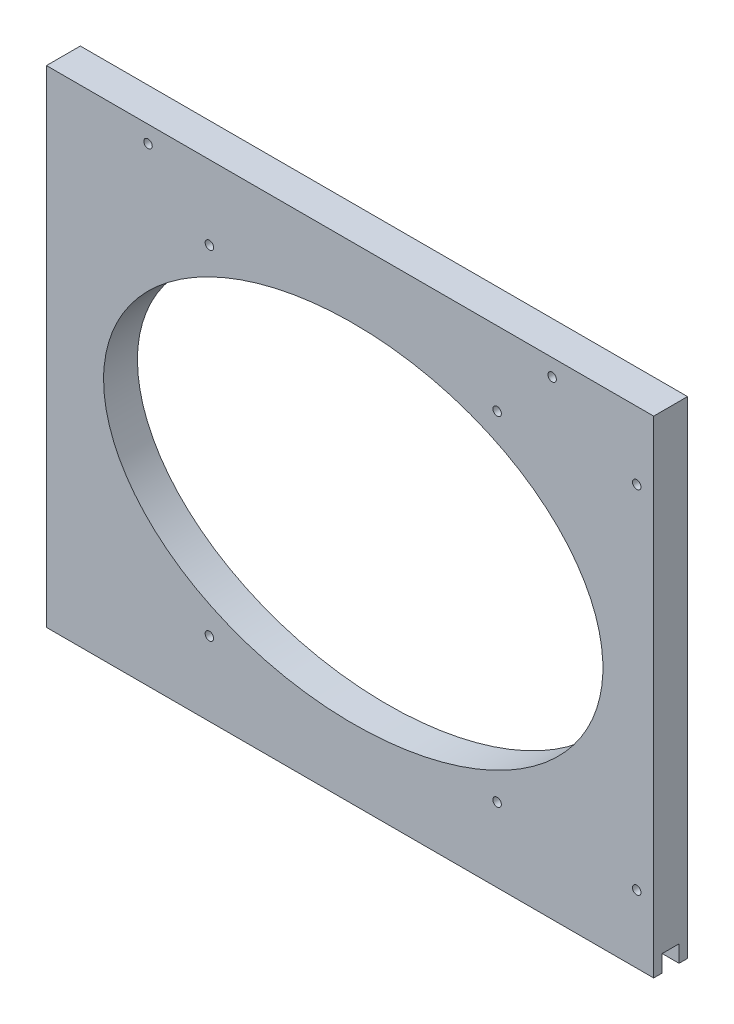
SolidWorks part; units mm, degrees
material "Pine"
ref_plane "Front Plane" through (0, 0, 0) normal (0, 0, 1) x (1, 0, 0)
ref_plane "Top Plane" through (0, 0, 0) normal (0, 1, 0) x (1, 0, 0)
ref_plane "Right Plane" through (0, 0, 0) normal (1, 0, 0) x (0, 0, -1)
sketch "Sketch1" plane through (0, 0, 0) normal (0, 0, 1) x (1, 0, 0)
  line L0 (-5300.6625, 1520.825) -> (-5451.475, 1520.825)
  line L1 (-5456.2375, 1384.3) -> (-5456.2375, 1516.0625)
  line L2 (-5557.8375, 1546.225) -> (-5194.3, 1546.225)
  line L3 (-5557.8375, 1539.875) -> (-5194.3, 1539.875)
  line L4 (-5297.4875, 1377.95) -> (-5454.65, 1377.95)
  line L5 (-5291.1375, 1384.3) -> (-5291.1375, 1516.0625)
  line L6 (-5300.6625, 1525.5875) -> (-5451.475, 1525.5875)
  line L7 (-5461, 1384.3) -> (-5461, 1516.0625)
  line L8 (-5297.4875, 1382.7125) -> (-5454.65, 1382.7125)
  line L9 (-5295.9, 1384.3) -> (-5295.9, 1516.0625)
  line L10 (-5740.4, 998.5375) -> (-5740.4, 1181.1)
  line L11 (-5740.4, 1181.1) -> (-5512.5938, 1181.1)
  line L12 (-5512.5938, 1181.1) -> (-5512.5938, 998.5375)
  line L13 (-5512.5938, 998.5375) -> (-5740.4, 998.5375)
  line L14 (-5258.5938, 1181.1) -> (-5486.4, 1181.1)
  line L15 (-5258.5938, 998.5375) -> (-5258.5938, 1181.1)
  line L16 (-5486.4, 998.5375) -> (-5258.5938, 998.5375)
  line L17 (-5486.4, 1181.1) -> (-5486.4, 998.5375)
  line L18 (-5740.4, 898.525) -> (-5011.7375, 898.525)
  line L19 (-5168.1062, 1384.3) -> (-5168.1062, 1392.2375)
  line L20 (-5176.0437, 1400.175) -> (-5245.8937, 1400.175)
  line L21 (-5253.8313, 1392.2375) -> (-5253.8313, 1384.3)
  line L22 (-5451.475, 1512.8875) -> (-5451.475, 1384.3)
  line L23 (-5303.8375, 1516.0625) -> (-5448.3, 1516.0625)
  line L24 (-5498.3062, 1384.3) -> (-5451.475, 1384.3)
  line L25 (-5253.8313, 1384.3) -> (-5300.6625, 1384.3)
  line L26 (-5584.0312, 1384.3) -> (-5740.4, 1384.3)
  line L27 (-5564.1875, 1536.7) -> (-5740.4, 1536.7)
  line L28 (-5740.4, 1357.3125) -> (-5740.4, 1206.5)
  line L29 (-5011.7375, 1357.3125) -> (-5740.4, 1357.3125)
  line L30 (-5011.7375, 1206.5) -> (-5011.7375, 1357.3125)
  line L31 (-5740.4, 1206.5) -> (-5011.7375, 1206.5)
  line L32 (-4765.675, 1549.4) -> (-4978.4, 1549.4)
  line L33 (-4765.675, 1397) -> (-4765.675, 1549.4)
  line L34 (-4978.4, 1397) -> (-4765.675, 1397)
  line L35 (-4978.4, 1549.4) -> (-4978.4, 1397)
  line L36 (-4765.675, 1371.6) -> (-4978.4, 1371.6)
  line L37 (-4765.675, 1219.2) -> (-4765.675, 1371.6)
  line L38 (-4978.4, 1219.2) -> (-4765.675, 1219.2)
  line L39 (-4978.4, 1371.6) -> (-4978.4, 1219.2)
  line L40 (-5284.7875, 803.275) -> (-5272.0875, 803.275)
  line L41 (-5187.95, 1536.7) -> (-5011.7375, 1536.7)
  line L42 (-5300.6625, 1384.3) -> (-5300.6625, 1512.8875)
  line L43 (-5740.4, 1536.7) -> (-5740.4, 1384.3)
  line L44 (-5557.8375, 1536.7) -> (-5557.8375, 1549.4)
  line L45 (-5557.8375, 1549.4) -> (-5194.3, 1549.4)
  line L46 (-5194.3, 1549.4) -> (-5194.3, 1536.7)
  line L47 (-5011.7375, 1536.7) -> (-5011.7375, 1384.3)
  line L48 (-5011.7375, 1384.3) -> (-5168.1062, 1384.3)
  line L49 (-5498.3062, 1384.3) -> (-5498.3062, 1392.2375)
  line L50 (-5506.2437, 1400.175) -> (-5576.0938, 1400.175)
  line L51 (-5584.0312, 1392.2375) -> (-5584.0312, 1384.3)
  line L52 (-5740.4, 660.4) -> (-5740.4, 898.525)
  line L53 (-5011.7375, 898.525) -> (-5011.7375, 660.4)
  line L54 (-5011.7375, 660.4) -> (-5740.4, 660.4)
  line L55 (-5291.1375, 803.275) -> (-5291.1375, 752.475)
  line L56 (-5265.7375, 752.475) -> (-5265.7375, 803.275)
  line L57 (-5284.7875, 752.475) -> (-5272.0875, 752.475)
  arc A0 (-5451.475, 1520.825) -> (-5456.2375, 1516.0625) centre (-5451.475, 1516.0625) ccw
  arc A1 (-5461, 1384.3) -> (-5454.65, 1377.95) centre (-5454.65, 1384.3) ccw
  arc A2 (-5297.4875, 1377.95) -> (-5291.1375, 1384.3) centre (-5297.4875, 1384.3) ccw
  circle A3 centre (-5037.9312, 1233.4875) radius 1.5875
  circle A4 centre (-5037.9312, 1328.7375) radius 1.5875
  circle A5 centre (-5714.2063, 1233.4875) radius 1.5875
  circle A6 centre (-5714.2063, 1328.7375) radius 1.5875
  circle A7 centre (-5018.0875, 1333.5) radius 1.5875
  circle A8 centre (-5018.0875, 1231.9) radius 1.5875
  circle A9 centre (-5734.05, 1231.9) radius 1.5875
  circle A10 centre (-5734.05, 1333.5) radius 1.5875
  circle A11 centre (-5734.05, 1511.3) radius 1.5875
  circle A12 centre (-5734.05, 1409.7) radius 1.5875
  circle A13 centre (-5018.0875, 1511.3) radius 1.5875
  circle A14 centre (-5018.0875, 1409.7) radius 1.5875
  arc A15 (-5557.8375, 1546.225) -> (-5557.8375, 1539.875) centre (-5557.8375, 1543.05) ccw
  arc A16 (-5194.3, 1539.875) -> (-5194.3, 1546.225) centre (-5194.3, 1543.05) ccw
  arc A17 (-5291.1375, 1516.0625) -> (-5300.6625, 1525.5875) centre (-5300.6625, 1516.0625) ccw
  arc A18 (-5451.475, 1525.5875) -> (-5461, 1516.0625) centre (-5451.475, 1516.0625) ccw
  arc A19 (-5456.2375, 1384.3) -> (-5454.65, 1382.7125) centre (-5454.65, 1384.3) ccw
  arc A20 (-5297.4875, 1382.7125) -> (-5295.9, 1384.3) centre (-5297.4875, 1384.3) ccw
  arc A21 (-5295.9, 1516.0625) -> (-5300.6625, 1520.825) centre (-5300.6625, 1516.0625) ccw
  circle A22 centre (-5702.3, 892.175) radius 1.5875
  circle A23 centre (-5734.05, 860.425) radius 1.5875
  circle A24 centre (-5474.8906, 892.175) radius 1.5875
  circle A25 centre (-5277.2469, 892.175) radius 1.5875
  circle A26 centre (-5049.8375, 892.175) radius 1.5875
  circle A27 centre (-5018.0875, 860.425) radius 1.5875
  circle A28 centre (-5296.6938, 1174.75) radius 1.5875
  circle A29 centre (-5448.3, 1174.75) radius 1.5875
  circle A30 centre (-5264.9437, 1155.7) radius 1.5875
  circle A31 centre (-5264.9437, 1023.9375) radius 1.5875
  circle A32 centre (-5518.9438, 1155.7) radius 1.5875
  circle A33 centre (-5518.9438, 1023.9375) radius 1.5875
  circle A34 centre (-5702.3, 1004.8875) radius 1.5875
  circle A35 centre (-5550.6937, 1004.8875) radius 1.5875
  arc A36 (-5576.0938, 1400.175) -> (-5584.0312, 1392.2375) centre (-5576.0938, 1392.2375) ccw
  arc A37 (-5168.1062, 1392.2375) -> (-5176.0437, 1400.175) centre (-5176.0437, 1392.2375) ccw
  arc A38 (-5245.8937, 1400.175) -> (-5253.8313, 1392.2375) centre (-5245.8937, 1392.2375) ccw
  arc A39 (-5448.3, 1516.0625) -> (-5451.475, 1512.8875) centre (-5448.3, 1512.8875) ccw
  arc A40 (-5284.7875, 803.275) -> (-5291.1375, 803.275) centre (-5287.9625, 803.275) ccw
  circle A41 centre (-5679.2812, 1026.3187) radius 1.5875
  circle A42 centre (-5679.2812, 1153.3187) radius 1.5875
  circle A43 centre (-5571.3313, 1153.3187) radius 1.5875
  circle A44 centre (-5571.3313, 1026.3187) radius 1.5875
  circle A45 centre (-5317.3312, 1153.3187) radius 1.5875
  circle A46 centre (-5317.3312, 1026.3187) radius 1.5875
  circle A47 centre (-5425.2812, 1026.3187) radius 1.5875
  circle A48 centre (-5425.2812, 1153.3187) radius 1.5875
  arc A49 (-5194.3, 1536.7) -> (-5187.95, 1536.7) centre (-5191.125, 1536.7) ccw
  arc A50 (-5564.1875, 1536.7) -> (-5557.8375, 1536.7) centre (-5561.0125, 1536.7) ccw
  arc A51 (-5300.6625, 1512.8875) -> (-5303.8375, 1516.0625) centre (-5303.8375, 1512.8875) ccw
  arc A52 (-5498.3062, 1392.2375) -> (-5506.2437, 1400.175) centre (-5506.2437, 1392.2375) ccw
  circle A53 centre (-5712.46, 784.225) radius 4.7625
  arc A54 (-5272.0875, 752.475) -> (-5265.7375, 752.475) centre (-5268.9125, 752.475) ccw
  arc A55 (-5291.1375, 752.475) -> (-5284.7875, 752.475) centre (-5287.9625, 752.475) ccw
  circle A56 centre (-5182.3938, 684.2125) radius 3.175
  circle A57 centre (-5239.5437, 684.2125) radius 3.175
  circle A58 centre (-5512.5938, 684.2125) radius 3.175
  circle A59 centre (-5569.7437, 684.2125) radius 3.175
  circle A60 centre (-5474.8906, 666.75) radius 1.5875
  circle A61 centre (-5277.2469, 666.75) radius 1.5875
  circle A62 centre (-5734.05, 698.5) radius 1.5875
  circle A63 centre (-5702.3, 666.75) radius 1.5875
  circle A64 centre (-5049.8375, 666.75) radius 1.5875
  circle A65 centre (-5018.0875, 698.5) radius 1.5875
  circle A66 centre (-5713.73, 835.025) radius 4.7625
  circle A67 centre (-5712.46, 819.785) radius 4.7625
  circle A68 centre (-5712.46, 802.005) radius 4.7625
  circle A69 centre (-5714.2063, 1314.45) radius 3.175
  circle A70 centre (-5037.9312, 1314.45) radius 3.175
  arc A71 (-5265.7375, 803.275) -> (-5272.0875, 803.275) centre (-5268.9125, 803.275) ccw
  ellipse E0 centre (-5371.3062, 1089.8188) end of major axis (-5277.6438, 1089.8188) minor radius 65.0875
  ellipse E1 centre (-5625.3062, 1089.8188) end of major axis (-5531.6438, 1089.8188) minor radius 65.0875
sketch "Sketch2" plane through (0, 0, 0) normal (0, 0, 1) x (1, 0, 0)
  line L0 (-5258.5938, 1181.1) -> (-5258.5938, 998.5375)
  line L1 (-5258.5938, 998.5375) -> (-5486.4, 998.5375)
  line L2 (-5486.4, 998.5375) -> (-5486.4, 1181.1)
  line L3 (-5486.4, 1181.1) -> (-5258.5938, 1181.1)
extrude "Extrude1" add sketch "Sketch2" against normal blind 12.7
sketch "Sketch3" plane through (0, 0, 0) normal (0, 0, 1) x (1, 0, 0)
  line L0 (-5464.9688, 1089.8188) -> (-5277.6438, 1089.8188) construction
  line L1 (-5371.3062, 1154.9062) -> (-5371.3062, 1024.7313) construction
  circle A0 centre (-5448.3, 1174.75) radius 1.5875
  circle A1 centre (-5425.2812, 1153.3187) radius 1.5875
  circle A2 centre (-5296.6938, 1174.75) radius 1.5875
  circle A3 centre (-5317.3312, 1153.3187) radius 1.5875
  circle A4 centre (-5264.9437, 1155.7) radius 1.5875
  circle A5 centre (-5264.9437, 1023.9375) radius 1.5875
  circle A6 centre (-5317.3312, 1026.3187) radius 1.5875
  circle A7 centre (-5425.2812, 1026.3187) radius 1.5875
  ellipse E0 centre (-5371.3062, 1089.8188) end of major axis (-5464.9688, 1089.8188) minor radius 65.0875
extrude "Cut-Extrude1" cut sketch "Sketch3" against normal up to surface (12.7 mm away) up to face at (-5372.4969, 1089.8188, -12.7)
sketch "Sketch4" plane through (-5258.5938, 0, 0) normal (1, 0, 0) x (0, 0, -1)
  line L0 (6.35, 998.5375) -> (3.175, 998.5375)
  line L1 (12.7, 998.5375) -> (0, 998.5375) construction
  line L2 (3.175, 998.5375) -> (3.175, 1004.8875)
  line L3 (3.175, 1004.8875) -> (9.525, 1004.8875)
  line L4 (9.525, 1004.8875) -> (9.525, 998.5375)
  line L5 (9.525, 998.5375) -> (6.35, 998.5375)
extrude "Cut-Extrude2" cut sketch "Sketch4" against normal up to surface (227.8062 mm away) up to face at (-5486.4, 1089.8188, -6.35)
